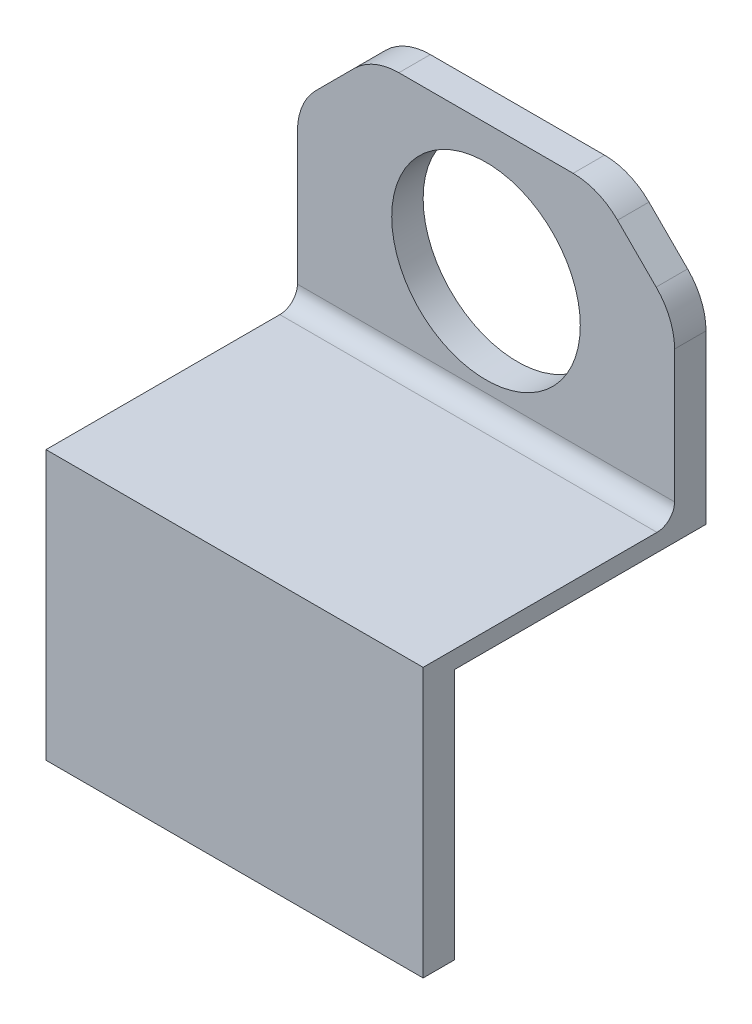
SolidWorks part; units mm, degrees
ref_plane "Front Plane" through (0, 0, 0) normal (0, 0, 1) x (1, 0, 0)
ref_plane "Top Plane" through (0, 0, 0) normal (0, 1, 0) x (1, 0, 0)
ref_plane "Right Plane" through (0, 0, 0) normal (1, 0, 0) x (0, 0, -1)
sketch "Sketch1" plane through (0, 0, 0) normal (0, 0, 1) x (1, 0, 0)
  line L1 (-19.05, 12.7) -> (19.05, 12.7)
  line L2 (-19.05, 12.7) -> (-19.05, -12.7)
  line L3 (-19.05, -12.7) -> (19.05, -12.7)
  line L4 (19.05, 12.7) -> (19.05, -12.7)
  line L5 (-19.05, 12.7) -> (19.05, -12.7) construction
  line L6 (-19.05, -12.7) -> (19.05, 12.7) construction
  point P0 (0, 0)
  dimension "D1" = 38.1
  dimension "D2" = 25.4
extrude "Boss-Extrude1" add sketch "Sketch1" along normal mid plane 3.175
sketch "Sketch2" plane through (0, 12.7, 0) normal (0, 1, 0) x (1, 0, 0)
  line L0 (19.05, -1.5875) -> (19.05, 1.5875) construction
  line L1 (-19.05, -1.5875) -> (19.05, -1.5875)
  line L2 (-19.05, -1.5875) -> (-19.05, 26.9875)
  line L3 (-19.05, 26.9875) -> (19.05, 26.9875)
  line L4 (19.05, -1.5875) -> (19.05, 26.9875)
  dimension "D1" = 28.575
extrude "Boss-Extrude2" add sketch "Sketch2" along normal blind 1.778
sketch "Sketch3" plane through (0, 14.478, 0) normal (0, 1, 0) x (1, 0, 0)
  line L0 (-19.05, 26.9875) -> (-19.05, -1.5875) construction
  line L1 (19.05, 26.9875) -> (-19.05, 26.9875)
  line L2 (19.05, 26.9875) -> (19.05, 23.8125)
  line L3 (19.05, 23.8125) -> (-19.05, 23.8125)
  line L4 (-19.05, 26.9875) -> (-19.05, 23.8125)
  dimension "D1" = 3.175
extrude "Boss-Extrude3" add sketch "Sketch3" along normal blind 25.4
sketch "Sketch5" plane through (0, 0, -23.8125) normal (0, 0, 1) x (1, 0, 0)
  circle A0 centre (0, 26.924) radius 9.525
  dimension "D1" = 19.05
  dimension "D2" = 26.924
extrude "Cut-Extrude1" cut sketch "Sketch5" against normal through all
chamfer "Chamfer1" distance 7.62 angle 45 2 edges at (-19.05, 39.878, -25.4) (19.05, 39.878, -25.4)
fillet "Fillet1" radius 6.35 4 edges at (-19.05, 32.258, -25.4) (-11.43, 39.878, -25.4) (19.05, 32.258, -25.4) (11.43, 39.878, -25.4)
fillet "Fillet2" radius 1.778 1 edges
